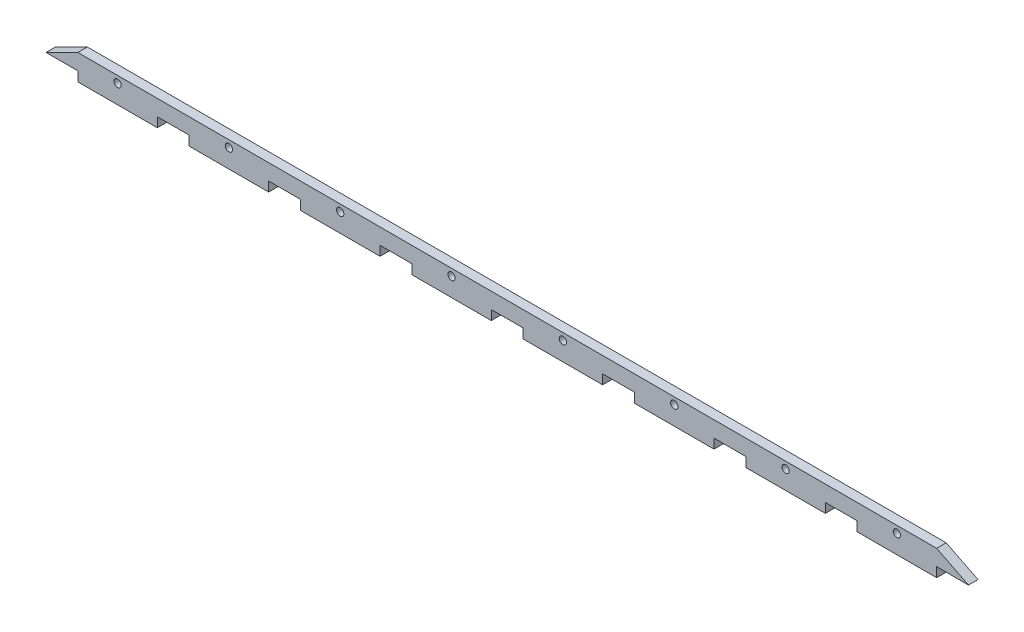
SolidWorks part; units mm, degrees
material "Thornel Mat VMA"
ref_plane "前视基准面" through (0, 0, 0) normal (0, 0, 1) x (1, 0, 0)
ref_plane "上视基准面" through (0, 0, 0) normal (0, 1, 0) x (1, 0, 0)
ref_plane "右视基准面" through (0, 0, 0) normal (1, 0, 0) x (0, 0, -1)
sketch "草图1" plane through (0, 0, 0) normal (0, 0, 1) x (1, 0, 0)
  line L0 (0, 0) -> (10, 5)
  line L1 (10, 5) -> (280, 5)
  line L2 (280, 5) -> (290, 0)
  line L3 (0, 0) -> (10, 0)
  line L4 (10, 0) -> (10, -3)
  line L5 (10, -3) -> (35, -3)
  line L6 (35, -3) -> (35, 0)
  line L7 (35, 0) -> (45, 0)
  line L8 (45, 0) -> (45, -3)
  line L9 (45, -3) -> (70, -3)
  line L10 (70, -3) -> (70, 0)
  line L11 (70, 0) -> (80, 0)
  line L12 (80, 0) -> (80, -3)
  line L13 (80, -3) -> (105, -3)
  line L14 (105, -3) -> (105, 0)
  line L15 (105, 0) -> (115, 0)
  line L16 (115, 0) -> (115, -3)
  line L17 (115, -3) -> (140, -3)
  line L18 (140, -3) -> (140, 0)
  line L19 (140, 0) -> (150, 0)
  line L20 (150, 0) -> (150, -3)
  line L21 (150, -3) -> (175, -3)
  line L22 (175, -3) -> (175, 0)
  line L23 (175, 0) -> (185, 0)
  line L24 (185, 0) -> (185, -3)
  line L25 (185, -3) -> (210, -3)
  line L26 (210, -3) -> (210, 0)
  line L27 (210, 0) -> (220, 0)
  line L28 (220, 0) -> (220, -3)
  line L29 (220, -3) -> (245, -3)
  line L30 (245, -3) -> (245, 0)
  line L31 (245, 0) -> (255, 0)
  line L32 (255, 0) -> (255, -3)
  line L33 (255, -3) -> (280, -3)
  line L34 (280, -3) -> (280, 0)
  line L35 (280, 0) -> (290, 0)
  line L39 (315, -3) -> (315, 0) [skipped]
  line L40 (290, -3) -> (315, -3) [skipped]
  line L41 (290, 0) -> (290, -3) [skipped]
  dimension "D2" = 10
  dimension "D3" = 25
  dimension "D4" = 3
  dimension "D6" = 5
  dimension "D5" = 9
extrude "凸台-拉伸1" add sketch "草图1" along normal blind 3
sketch "草图2" plane through (0, 0, 3) normal (0, 0, 1) x (1, 0, 0)
  line L0 (280, 5) -> (10, 5) construction
  line L1 (22.5, -3) -> (22.5, 5) construction
  line L2 (10, -3) -> (35, -3) construction
  line L3 (57.5, -3) -> (57.5, 5) construction
  line L4 (92.5, -3) -> (92.5, 5) construction
  line L5 (127.5, -3) -> (127.5, 5) construction
  line L6 (162.5, -3) -> (162.5, 5) construction
  line L7 (197.5, -3) -> (197.5, 5) construction
  line L8 (232.5, -3) -> (232.5, 5) construction
  line L9 (267.5, -3) -> (267.5, 5) construction
  circle A0 centre (22.5, 2.85) radius 1.15
  circle A1 centre (57.5, 2.85) radius 1.15
  circle A2 centre (92.5, 2.85) radius 1.15
  circle A3 centre (127.5, 2.85) radius 1.15
  circle A4 centre (162.5, 2.85) radius 1.15
  circle A5 centre (197.5, 2.85) radius 1.15
  circle A6 centre (232.5, 2.85) radius 1.15
  circle A7 centre (267.5, 2.85) radius 1.15
  dimension "D1" = 2.3
  dimension "D2" = 2.15
  dimension "D3" = 8
extrude "切除-拉伸1" cut sketch "草图2" against normal through all
